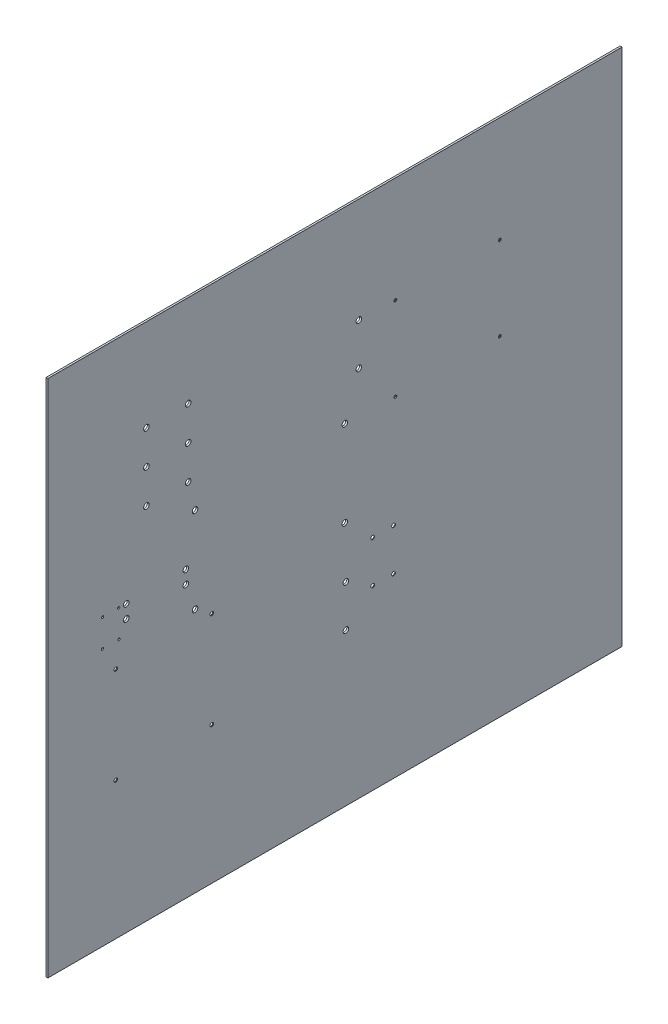
SolidWorks part; units mm, degrees
material "6061-T6 (SS)"
ref_plane "Front Plane" through (0, 0, 0) normal (0, 0, 1) x (1, 0, 0)
ref_plane "Top Plane" through (0, 0, 0) normal (0, 1, 0) x (1, 0, 0)
ref_plane "Right Plane" through (0, 0, 0) normal (1, 0, 0) x (0, 0, -1)
sketch "Sketch1" plane through (0, 0, 0) normal (1, 0, 0) x (0, 0, -1)
  line L1 (0, 0) -> (698.6905, 0)
  line L2 (0, 0) -> (0, 631.825)
  line L3 (0, 631.825) -> (698.6905, 631.825)
  line L4 (698.6905, 0) -> (698.6905, 631.825)
  line L5 (0, 0) -> (698.6905, 631.825) construction
  line L6 (0, 631.825) -> (698.6905, 0) construction
  point P4 (349.3452, 315.9125)
  dimension "D1" = 631.825
  dimension "D2" = 698.6905
extrude "Boss-Extrude1" add sketch "Sketch1" along normal blind 2.286
sketch "Sketch2" plane through (2.286, 0, 0) normal (1, 0, 0) x (0, 0, -1)
  line L0 (0, 631.825) -> (0, 0) construction
  line L1 (422.91, 401.32) -> (549.91, 401.32) construction
  line L2 (422.91, 401.32) -> (422.91, 502.92) construction
  line L3 (422.91, 502.92) -> (549.91, 502.92) construction
  line L4 (549.91, 401.32) -> (549.91, 502.92) construction
  line L5 (422.91, 401.32) -> (549.91, 502.92) construction
  line L6 (422.91, 502.92) -> (549.91, 401.32) construction
  line L7 (0, 0) -> (698.6905, 0) construction
  line L9 (82.55, 167.2844) -> (199.55, 167.2844) construction
  line L10 (82.55, 167.2844) -> (82.55, 284.2844) construction
  line L11 (82.55, 284.2844) -> (199.55, 284.2844) construction
  line L12 (199.55, 167.2844) -> (199.55, 284.2844) construction
  line L13 (82.55, 167.2844) -> (199.55, 284.2844) construction
  line L14 (82.55, 284.2844) -> (199.55, 167.2844) construction
  line L15 (66.588, 347.054) -> (86.138, 347.054) construction
  line L16 (86.138, 347.054) -> (86.438, 313.654) construction
  line L17 (86.438, 313.654) -> (66.288, 313.654) construction
  line L18 (66.288, 313.654) -> (66.588, 347.054) construction
  line L19 (119.911, 437.406) -> (170.711, 437.406) construction
  line L20 (119.911, 478.681) -> (170.711, 478.681) construction
  line L21 (119.911, 519.956) -> (170.711, 519.956) construction
  line L34 (66.588, 347.054) -> (64.588, 347.054) construction
  line L35 (66.588, 347.054) -> (66.588, 349.054) construction
  line L36 (66.588, 349.054) -> (64.588, 349.054) construction
  line L39 (362.727, 185.332) -> (362.727, 236.132) construction
  line L46 (95.386, 330.685) -> (167.886, 330.685) construction
  line L47 (95.386, 330.685) -> (95.386, 346.685) construction
  line L48 (95.386, 346.685) -> (167.886, 346.685) construction
  line L49 (167.886, 330.685) -> (167.886, 346.685) construction
  line L50 (95.386, 330.685) -> (167.886, 346.685) construction
  line L51 (95.386, 346.685) -> (167.886, 330.685) construction
  line L52 (378.46, 453.39) -> (378.46, 504.19) construction
  line L53 (179.07, 299.08) -> (361.3404, 299.08) construction
  line L54 (179.07, 299.08) -> (179.07, 403.474) construction
  line L55 (179.07, 403.474) -> (361.3404, 403.474) construction
  line L56 (361.3404, 299.08) -> (361.3404, 403.474) construction
  line L57 (179.07, 299.08) -> (361.3404, 403.474) construction
  line L58 (179.07, 403.474) -> (361.3404, 299.08) construction
  circle A0 centre (422.91, 401.32) radius 1.0795 construction
  circle A1 centre (422.91, 502.92) radius 1.0795 construction
  circle A2 centre (549.91, 502.92) radius 1.0795 construction
  circle A3 centre (549.91, 401.32) radius 1.0795 construction
  point P4 (486.41, 452.12)
  point P17 (141.05, 225.7844)
  point P30 (76.363, 347.054)
  point P47 (76.363, 313.654)
  point P52 (131.636, 338.685)
  point P59 (270.2052, 351.277)
  dimension "D4" = 2.159
  dimension "D1" = 101.6
  dimension "D2" = 127
  dimension "D5" = 401.32
  dimension "D6" = 117
  dimension "D7" = 117
  dimension "D8" = 422.91
  dimension "D9" = 50.8
  dimension "D10" = 66.588
  dimension "D11" = 19.55
  dimension "D12" = 20.15
  dimension "D13" = 185.332
  dimension "D14" = 313.654
  dimension "D15" = 50.8
  dimension "D16" = 3
  dimension "D17" = 437.406
  dimension "D18" = 33.4
  dimension "D23" = 119.911
  dimension "D24" = 362.727
  dimension "D25" = 50.8
  dimension "D26" = 2
  dimension "D27" = 2
  dimension "D28" = 453.39
  dimension "D29" = 378.46
  dimension "D32" = 82.55
  dimension "D34" = 16
  dimension "D35" = 72.5
  dimension "D36" = 95.386
  dimension "D37" = 330.685
  dimension "D38" = 167.2844
  dimension "D39" = 41.275
  dimension "D41" = 104.394
  dimension "D42" = 182.2704
  dimension "D43" = 179.07
  dimension "D44" = 299.08
sketch "Sketch3" plane through (2.286, 0, 0) normal (1, 0, 0) x (0, 0, -1)
  circle A0 centre (179.07, 299.08) radius 3.3734
  circle A1 centre (179.07, 403.474) radius 3.3734
  circle A2 centre (361.3404, 403.474) radius 3.3734
  circle A3 centre (361.3404, 299.08) radius 3.3734
  circle A4 centre (119.911, 437.406) radius 3.3734
  circle A5 centre (170.711, 437.406) radius 3.3734
  circle A6 centre (119.911, 478.681) radius 3.3734
  circle A7 centre (170.711, 478.681) radius 3.3734
  circle A8 centre (119.911, 519.956) radius 3.3734
  circle A9 centre (170.711, 519.956) radius 3.3734
  circle A10 centre (362.727, 185.332) radius 3.3734
  circle A11 centre (362.727, 236.132) radius 3.3734
  circle A12 centre (378.46, 453.39) radius 3.3734
  circle A13 centre (378.46, 504.19) radius 3.3734
  circle A14 centre (95.386, 330.685) radius 3.3734
  circle A15 centre (95.386, 346.685) radius 3.3734
  circle A16 centre (167.886, 346.685) radius 3.3734
  circle A17 centre (167.886, 330.685) radius 3.3734
  circle A18 centre (82.55, 167.2844) radius 2.5797 construction
  circle A19 centre (82.55, 284.2844) radius 2.5797 construction
  circle A20 centre (199.55, 284.2844) radius 2.5797 construction
  circle A21 centre (199.55, 167.2844) radius 2.5797 construction
  dimension "D1" = 6.7469
  dimension "D2" = 6.7469
  dimension "D3" = 6.7469
  dimension "D4" = 5.1594
extrude "Cut-Extrude1" cut sketch "Sketch3" against normal through all
hole_wizard "CSK for #6 Flat Head Machine Screw1" positions "Sketch4" profile "Sketch5" countersink size "#6" standard "ANSI Inch" end condition up to next
sketch "Sketch4" plane through (0, 0, 0) normal (1, 0, 0) x (0, 0, -1)
  point P0 (82.55, 167.2844)
  point P3 (199.55, 167.2844)
  point P6 (199.55, 284.2844)
  point P9 (82.55, 284.2844)
sketch "Sketch5" plane through (0, 167.2844, -82.55) normal (0, 1, 0) x (0, 0, 1)
  line L0 (0, 0) -> (0, 2.286)
  line L1 (0, 2.286) -> (2.1526, 2.286)
  line L2 (2.1526, 2.286) -> (2.1526, 1.5998)
  line L3 (2.1526, 1.5998) -> (3.5433, 0)
  line L5 (3.5433, 0) -> (0, 0)
  line L6 (-2.1526, 1.5998) -> (-3.5433, 0) construction
  line L11 (0, -6.35) -> (0, 107.95) construction
  dimension "Thru Hole Dia." = 4.3053
  dimension "Thru Hole Depth" = 2.286
  dimension "Near C'Sink Dia." = 7.0866
  dimension "Near C'Sink Angle" = 82
hole_wizard "CSK for #2 Flat Head Machine Screw1" positions "Sketch9" profile "Sketch10" countersink size "#2" standard "ANSI Inch" end condition up to next
sketch "Sketch9" plane through (0, 0, 0) normal (-1, 0, 0) x (0, 0, 1)
  line L0 (-66.288, 313.654) -> (-66.588, 347.054) construction
  line L1 (-66.588, 347.054) -> (-86.138, 347.054) construction
  point P0 (-66.588, 347.054)
  point P2 (-86.138, 347.054)
  point P4 (-86.438, 313.654)
  point P6 (-66.288, 313.654)
sketch "Sketch10" plane through (0, 347.054, -66.588) normal (0, 1, 0) x (0, 0, 1)
  line L0 (0, 0) -> (0, 2.286)
  line L1 (0, 2.286) -> (1.3525, 2.286)
  line L2 (1.3525, 2.286) -> (1.3525, 0.9569)
  line L3 (1.3525, 0.9569) -> (2.1844, 0)
  line L5 (2.1844, 0) -> (0, 0)
  line L6 (-1.3525, 0.9569) -> (-2.1844, 0) construction
  line L11 (0, -6.35) -> (0, 107.95) construction
  dimension "Thru Hole Dia." = 2.7051
  dimension "Thru Hole Depth" = 2.286
  dimension "Near C'Sink Dia." = 4.3688
  dimension "Near C'Sink Angle" = 82
hole_wizard "CSK for #4 Flat Head Machine Screw1" positions "Sketch11" profile "Sketch12" countersink size "#4" standard "ANSI Inch" end condition up to next
sketch "Sketch11" plane through (0, 0, 0) normal (-1, 0, 0) x (0, 0, 1)
  point P0 (-422.91, 502.92)
  point P2 (-422.91, 401.32)
  point P4 (-549.91, 401.32)
  point P6 (-549.91, 502.92)
sketch "Sketch12" plane through (0, 502.92, -422.91) normal (0, 1, 0) x (0, 0, 1)
  line L0 (0, 0) -> (0, 2.286)
  line L1 (0, 2.286) -> (1.7272, 2.286)
  line L2 (1.7272, 2.286) -> (1.7272, 1.3003)
  line L3 (1.7272, 1.3003) -> (2.8575, 0)
  line L5 (2.8575, 0) -> (0, 0)
  line L6 (-1.7272, 1.3003) -> (-2.8575, 0) construction
  line L11 (0, -6.35) -> (0, 107.95) construction
  dimension "Thru Hole Dia." = 3.4544
  dimension "Thru Hole Depth" = 2.286
  dimension "Near C'Sink Dia." = 5.715
  dimension "Near C'Sink Angle" = 82
hole_wizard "CSK for #8 Flat Head Machine Screw1" positions "Sketch13" profile "Sketch14" countersink size "#8" standard "ANSI Inch" end condition through all
sketch "Sketch13" plane through (0, 0, 0) normal (1, 0, 0) x (0, 0, -1)
  line L1 (395.2875, 215.9) -> (420.6875, 215.9)
  line L2 (395.2875, 215.9) -> (395.2875, 266.7)
  line L3 (395.2875, 266.7) -> (420.6875, 266.7)
  line L4 (420.6875, 215.9) -> (420.6875, 266.7)
  line L5 (698.6905, 0) -> (698.6905, 631.825) construction
  line L6 (0, 0) -> (698.6905, 0) construction
  point P2 (395.2875, 215.9)
  point P3 (420.6875, 266.7)
  point P6 (395.2875, 266.7)
  point P7 (420.6875, 215.9)
  dimension "D1" = 50.8
  dimension "D2" = 25.4
  dimension "D3" = 278.003
  dimension "D4" = 215.9
sketch "Sketch14" plane through (0, 215.9, -395.2875) normal (0, 1, 0) x (0, 0, 1)
  line L0 (0, 0) -> (0, 2.286)
  line L1 (0, 2.286) -> (2.2479, 2.286)
  line L2 (2.2479, 2.286) -> (2.2479, 2.2645)
  line L3 (2.2479, 2.2645) -> (4.2164, 0)
  line L5 (4.2164, 0) -> (0, 0)
  line L6 (-2.2479, 2.2645) -> (-4.2164, 0) construction
  line L11 (0, -6.35) -> (0, 107.95) construction
  dimension "Thru Hole Dia." = 4.4958
  dimension "Thru Hole Depth" = 2.286
  dimension "Near C'Sink Dia." = 8.4328
  dimension "Near C'Sink Angle" = 82
